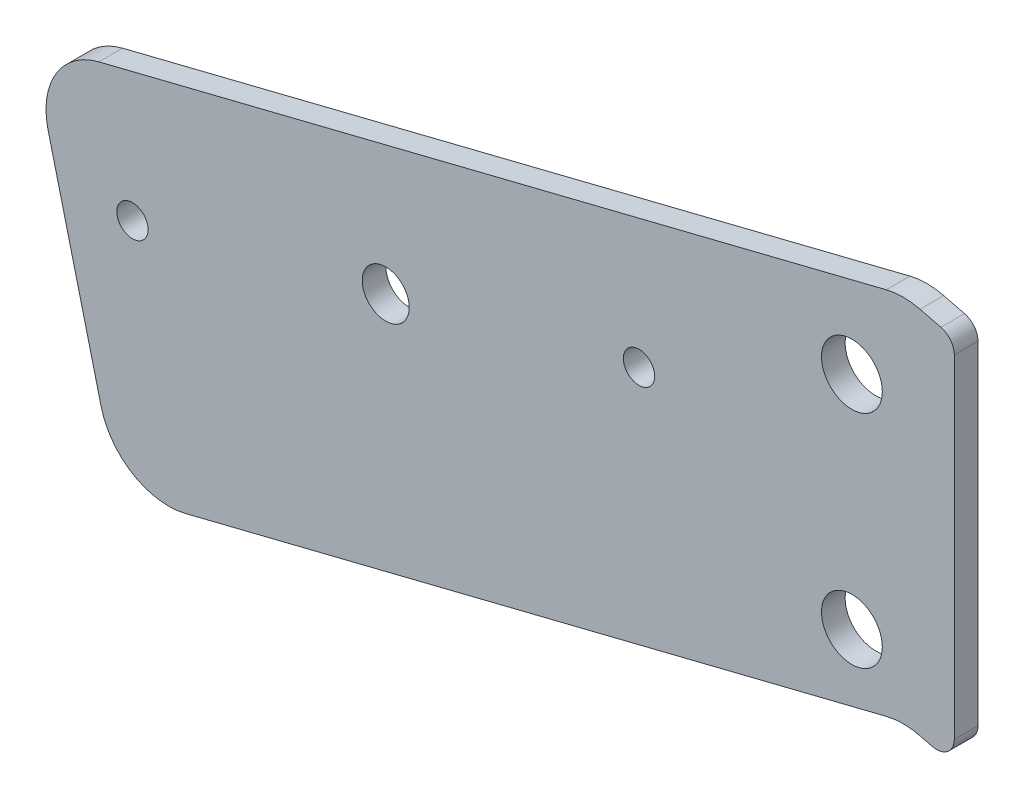
SolidWorks part; units mm, degrees
ref_plane "Front Plane" through (0, 0, 0) normal (0, 0, 1) x (1, 0, 0)
ref_plane "Top Plane" through (0, 0, 0) normal (0, 1, 0) x (1, 0, 0)
ref_plane "Right Plane" through (0, 0, 0) normal (1, 0, 0) x (0, 0, -1)
sketch "Sketch1" plane through (0, 0, 0) normal (0, 0, 1) x (1, 0, 0)
  line L0 (0, 0) -> (-82.5, -20.5696) construction
  line L1 (0, 0) -> (82.5, -20.5696) construction
  line L2 (-82.5, -20.5696) -> (82.5, -20.5696) construction
  line L3 (-82.5, -20.5696) -> (-74.3351, -53.317) construction
  line L5 (-74.3351, -53.317) -> (-37.949, -44.245) construction
  line L6 (-74.3351, -53.317) -> (-110.7212, -62.3891) construction
  line L8 (7.3483, -20.0488) -> (7.3483, -67.8899)
  line L9 (55, 0) -> (-55, 0) construction
  line L10 (-115.561, -45.0447) -> (-2.4192, -16.8353)
  line L11 (2.4192, -16.8353) -> (5.4228, -17.5842)
  line L13 (4.1938, -70.3544) -> (2.4192, -69.9119)
  line L14 (-2.4192, -69.9119) -> (-103.102, -95.015)
  line L15 (-115.2242, -87.7312) -> (-122.8447, -57.1669)
  line L16 (0, -20.5696) -> (0, -58.6696) construction
  line L17 (-7.366, -20.5696) -> (-7.366, -61.5696) construction
  arc A0 (-2.4192, -16.8353) -> (2.4192, -16.8353) centre (0, -26.5383) cw
  arc A1 (2.4192, -69.9119) -> (-2.4192, -69.9119) centre (0, -79.6149) ccw
  arc A4 (-103.102, -95.015) -> (-115.2242, -87.7312) centre (-105.5212, -85.312) cw
  arc A5 (-115.561, -45.0447) -> (-122.8447, -57.1669) centre (-113.1417, -54.7477) ccw
  arc A6 (4.1938, -70.3544) -> (7.3483, -67.8899) centre (4.8083, -67.8899) ccw
  arc A7 (5.4228, -17.5842) -> (7.3483, -20.0488) centre (4.8083, -20.0488) cw
  point P17 (-7.366, -29.8196)
  point P21 (0, -16.2322)
  point P24 (0, -69.3088)
  point P26 (7.3483, -71.1409)
  point P38 (7.3483, -18.0643)
  dimension "D13" = 10
  dimension "D12" = 2.54
  dimension "D1" = 165
  dimension "D2" = 18
  dimension "D3" = 152
  dimension "D4" = 33.75
  dimension "D6" = 37.5
  dimension "D7" = 37.5
  dimension "D9" = 5.08
  dimension "D10" = 33.5
  dimension "D11" = 48
  dimension "D14" = 7.366
  dimension "D15" = 41
  dimension "D16" = 31.75
extrude "Boss-Extrude1" add sketch "Sketch1" against normal blind 3.4036
hole_wizard "1/4 Clearance Hole1" positions "Sketch9" profile "Sketch10" hole size "1/4" standard "ANSI Inch" end condition through all
sketch "Sketch9" plane through (0, 0, 0) normal (0, 0, 1) x (1, 0, 0)
  point P0 (-74.3351, -53.317)
sketch "Sketch10" plane through (-74.3351, -53.317, 0) normal (1, 0, 0) x (0, -1, 0)
  line L0 (0, 0) -> (0, 3.4036)
  line L1 (0, 3.4036) -> (3.3782, 3.4036)
  line L2 (3.3782, 3.4036) -> (3.3782, 0)
  line L5 (3.3782, 0) -> (0, 0)
  line L11 (0, -6.35) -> (0, 107.95) construction
  dimension "Thru Hole Dia." = 6.7564
  dimension "Thru Hole Depth" = 3.4036
hole_wizard "M4 Clearance Hole1" positions "Sketch11" profile "Sketch12" hole size "M4" standard "ANSI Metric" end condition through all
sketch "Sketch11" plane through (0, 0, 0) normal (0, 0, 1) x (1, 0, 0)
  point P0 (-110.7212, -62.3891)
  point P3 (-37.949, -44.245)
sketch "Sketch12" plane through (-110.7212, -62.3891, 0) normal (1, 0, 0) x (0, -1, 0)
  line L0 (0, 0) -> (0, 3.4036)
  line L1 (0, 3.4036) -> (2.25, 3.4036)
  line L2 (2.25, 3.4036) -> (2.25, 0)
  line L5 (2.25, 0) -> (0, 0)
  line L11 (0, -6.35) -> (0, 107.95) construction
  dimension "Thru Hole Dia." = 4.5
  dimension "Thru Hole Depth" = 3.4036
hole_wizard "Hole for 1/4 300® SC Nuts (SP)1" positions "Sketch13" profile "Sketch14" hole size "1/4-20" standard "PEM® Inch" end condition through all
sketch "Sketch13" plane through (0, 0, 0) normal (0, 0, 1) x (1, 0, 0)
  point P20 (-7.366, -61.5696)
  point P23 (-7.366, -29.8196)
sketch "Sketch14" plane through (-7.366, -61.5696, 0) normal (1, 0, 0) x (0, -1, 0)
  line L0 (0, 0) -> (0, 3.4036)
  line L1 (0, 3.4036) -> (4.3688, 3.4036)
  line L2 (4.3688, 3.4036) -> (4.3688, 0)
  line L5 (4.3688, 0) -> (0, 0)
  line L11 (0, -6.35) -> (0, 107.95) construction
  dimension "Thru Hole Dia." = 8.7376
  dimension "Thru Hole Depth" = 3.4036
